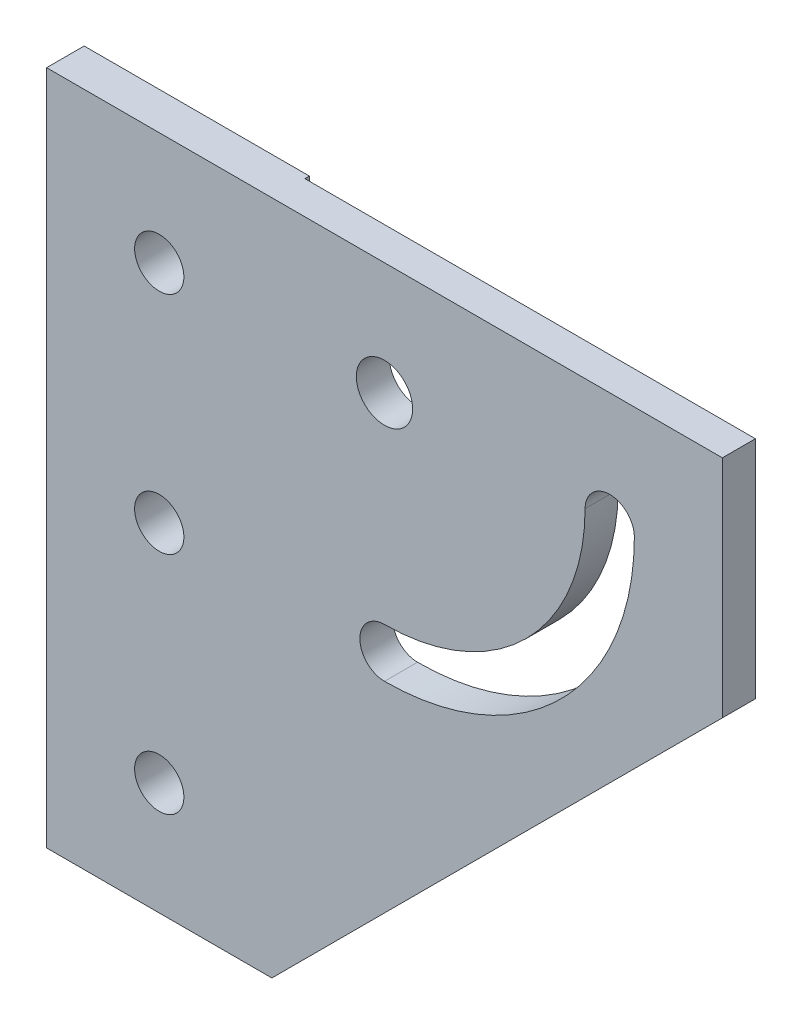
SolidWorks part; units mm, degrees
material "6105-T5 Aluminum"
ref_plane "Front Plane" through (0, 0, 0) normal (0, 0, 1) x (1, 0, 0)
ref_plane "Top Plane" through (0, 0, 0) normal (0, 1, 0) x (1, 0, 0)
ref_plane "Right Plane" through (0, 0, 0) normal (1, 0, 0) x (0, 0, -1)
ref_plane "Plane1" through (0, 0, 0.3684) normal (0, 0, 1) x (1, 0, 0)
sketch "Sketch1" plane through (0, 0, 0.3684) normal (0, 0, 1) x (1, 0, 0)
  line L0 (65.2268, 55.0078) -> (-49.0732, 55.0078)
  line L1 (-49.0732, 55.0078) -> (-49.0732, -59.2922)
  line L2 (-49.0732, -59.2922) -> (-10.9732, -59.2922)
  line L3 (-10.9732, -59.2922) -> (65.2268, 16.9078)
  line L4 (65.2268, 16.9078) -> (65.2268, 55.0078)
  dimension "D1" = 38.1
  dimension "D2" = 114.3
  dimension "D3" = 76.2
  dimension "D4" = 114.3
extrude "Boss-Extrude1" add sketch "Sketch1" against normal blind 5.588
sketch "Sketch2" plane through (0, 0, -5.2196) normal (0, 0, -1) x (-1, 0, 0)
  line L0 (49.0732, 55.0078) -> (49.0732, -59.2922)
  line L1 (49.0732, -59.2922) -> (10.9732, -59.2922)
  line L2 (10.9732, -59.2922) -> (10.9732, 55.0078)
  line L3 (10.9732, 55.0078) -> (49.0732, 55.0078)
  line L4 (-65.2268, 16.9078) -> (-65.2268, 55.0078) construction
  line L5 (49.0732, -59.2922) -> (10.9732, -59.2922) construction
  dimension "D1" = 76.2
  dimension "D2" = 114.3
  dimension "D3" = 114.3
extrude "Boss-Extrude2" add sketch "Sketch2" along normal blind 0.762
sketch "Sketch3" plane through (0, 0, -5.2196) normal (0, 0, -1) x (-1, 0, 0)
  line L0 (10.9732, 55.0078) -> (10.9732, -59.2922) construction
  line L1 (-65.2268, 55.0078) -> (10.9732, 55.0078) construction
  arc A0 (-42.0112, 35.9578) -> (-50.3424, 35.9578) centre (-46.1768, 35.9578) ccw
  arc A1 (-50.3424, 35.9578) -> (-8.0768, -6.3078) centre (-8.0768, 35.9578) ccw
  arc A2 (-8.0768, -6.3078) -> (-8.0768, 2.0234) centre (-8.0768, -2.1422) ccw
  arc A3 (-8.0768, 2.0234) -> (-42.0112, 35.9578) centre (-8.0768, 35.9578) cw
  dimension "D1" = 4.1656
  dimension "D2" = 42.2656
  dimension "D3" = 52.9844
  dimension "D4" = 52.9844
extrude "Cut-Extrude1" cut sketch "Sketch3" against normal through all
hole_wizard "Hole1" positions "Sketch5" profile "Sketch4" legacy
sketch "Sketch5" plane through (0, 0, -5.9816) normal (0, 0, -1) x (-1, 0, 0)
  point P0 (30.0232, -2.1422)
sketch "Sketch4" plane through (-30.0232, -2.1422, -5.9816) normal (1, 0, 0) x (0, 1, 0)
  line L0 (0, 0) -> (0, 6.35)
  line L1 (0, 6.35) -> (4.1656, 6.35)
  line L2 (4.1656, 6.35) -> (4.1656, 0)
  line L3 (4.1656, 0) -> (0, 0)
  line L4 (0, 110) -> (0, -10) construction
  dimension "Diameter" = 8.3312
  dimension "Depth" = 6.35
hole_wizard "Hole2" positions "Sketch7" profile "Sketch6" legacy
sketch "Sketch7" plane through (0, 0, -5.9816) normal (0, 0, -1) x (-1, 0, 0)
  point P0 (30.0232, 35.9578)
sketch "Sketch6" plane through (-30.0232, 35.9578, -5.9816) normal (1, 0, 0) x (0, 1, 0)
  line L0 (0, 0) -> (0, 6.35)
  line L1 (0, 6.35) -> (4.1656, 6.35)
  line L2 (4.1656, 6.35) -> (4.1656, 0)
  line L3 (4.1656, 0) -> (0, 0)
  line L4 (0, 110) -> (0, -10) construction
  dimension "Diameter" = 8.3312
  dimension "Depth" = 6.35
hole_wizard "Hole3" positions "Sketch9" profile "Sketch8" legacy
sketch "Sketch9" plane through (0, 0, -5.9816) normal (0, 0, -1) x (-1, 0, 0)
  point P0 (30.0232, -40.2422)
sketch "Sketch8" plane through (-30.0232, -40.2422, -5.9816) normal (1, 0, 0) x (0, 1, 0)
  line L0 (0, 0) -> (0, 6.35)
  line L1 (0, 6.35) -> (4.1656, 6.35)
  line L2 (4.1656, 6.35) -> (4.1656, 0)
  line L3 (4.1656, 0) -> (0, 0)
  line L4 (0, 110) -> (0, -10) construction
  dimension "Diameter" = 8.3312
  dimension "Depth" = 6.35
hole_wizard "M8 Clearance Hole1" positions "Sketch11" profile "Sketch10" hole size "M8" standard "Ansi Metric"
sketch "Sketch11" plane through (0, 0, 0.3684) normal (0, 0, 1) x (1, 0, 0)
  point P0 (8.0768, 35.9578)
sketch "Sketch10" plane through (8.0768, 35.9578, 0.3684) normal (1, 0, 0) x (0, -1, 0)
  line L0 (0, 0) -> (0, 6.35)
  line L1 (0, 6.35) -> (4.7625, 6.35)
  line L2 (4.7625, 6.35) -> (4.7625, 0)
  line L5 (4.7625, 0) -> (0, 0)
  line L11 (0, -6.35) -> (0, 107.95) construction
  dimension "Thru Hole Dia." = 9.525
  dimension "Thru Hole Depth" = 6.35
